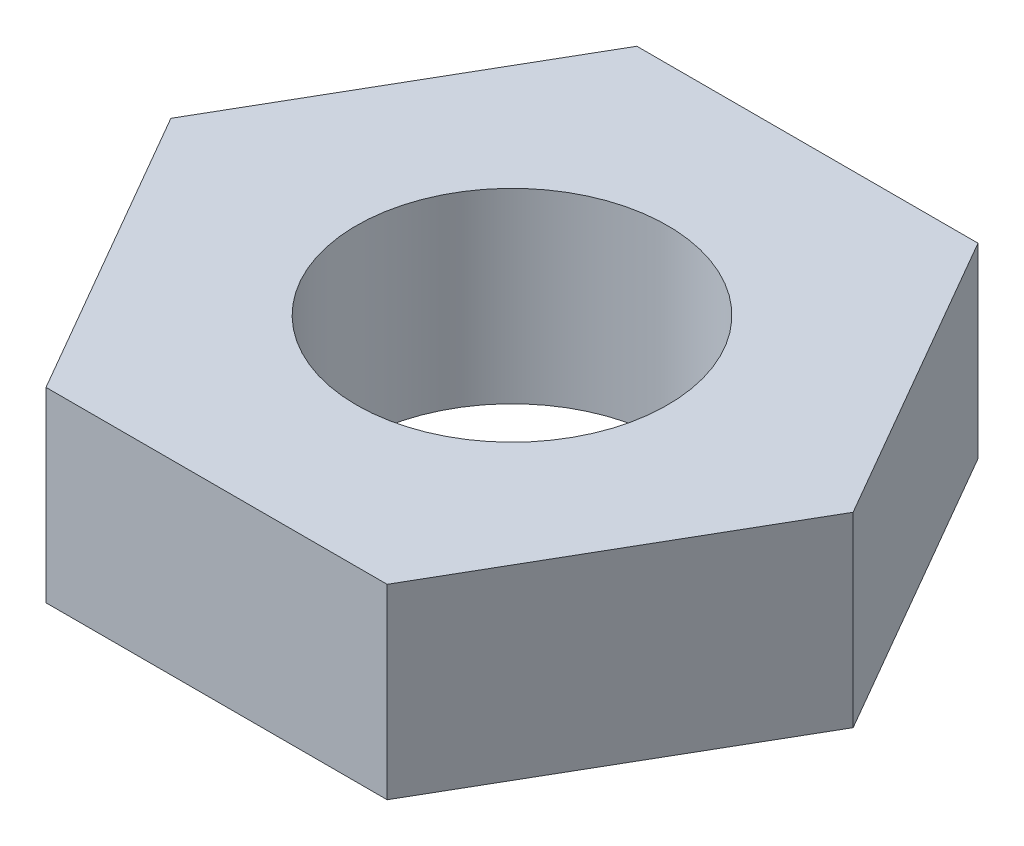
SolidWorks part; units mm, degrees
material "Nylon 101"
ref_plane "Front Plane" through (0, 0, 0) normal (0, 0, 1) x (1, 0, 0)
ref_plane "Top Plane" through (0, 0, 0) normal (0, 1, 0) x (1, 0, 0)
ref_plane "Right Plane" through (0, 0, 0) normal (1, 0, 0) x (0, 0, -1)
sketch "Sketch1" plane through (0, 0, 0) normal (0, 1, 0) x (1, 0, 0)
  line L1 (1.097, 1.9) -> (-1.097, 1.9)
  line L2 (-1.097, 1.9) -> (-2.1939, 0)
  line L3 (-2.1939, 0) -> (-1.097, -1.9)
  line L4 (-1.097, -1.9) -> (1.097, -1.9)
  line L5 (1.097, -1.9) -> (2.1939, 0)
  line L6 (2.1939, 0) -> (1.097, 1.9)
  circle A0 centre (0, 0) radius 1.9 construction
  circle A1 centre (0, 0) radius 1
  dimension "D2" = 2
  dimension "D1" = 3.8
extrude "Boss-Extrude1" add sketch "Sketch1" along normal blind 1.2
